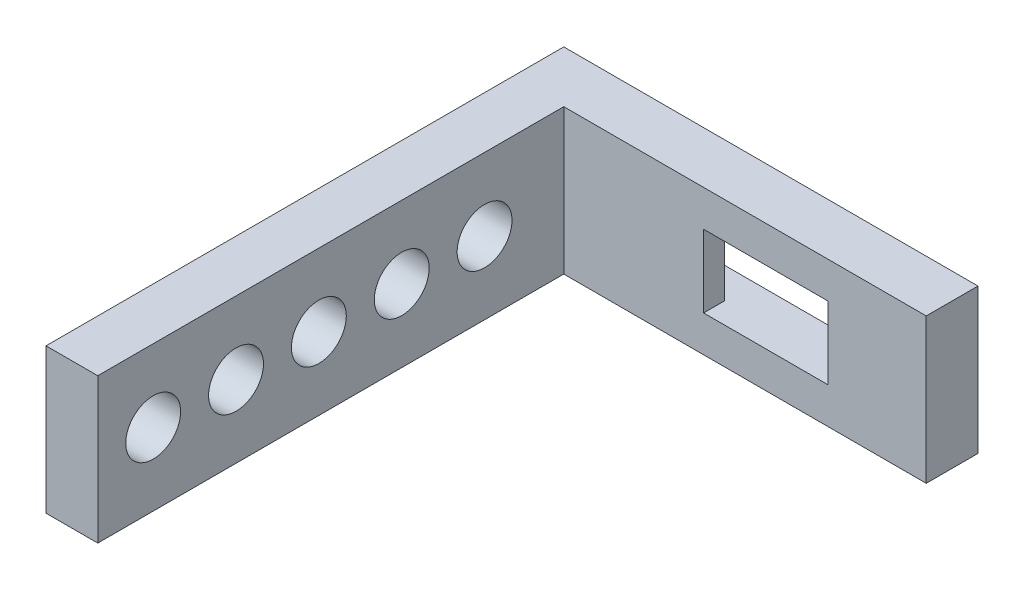
SolidWorks part; units mm, degrees
ref_plane "Front Plane" through (0, 0, 0) normal (0, 0, 1) x (1, 0, 0)
ref_plane "Top Plane" through (0, 0, 0) normal (0, 1, 0) x (1, 0, 0)
ref_plane "Right Plane" through (0, 0, 0) normal (1, 0, 0) x (0, 0, -1)
sketch "Sketch1" plane through (0, 0, 0) normal (0, 1, 0) x (1, 0, 0)
  line L2 (6.5891, 0) -> (10, 0)
  line L8 (0, 9) -> (11.5891, 9)
  line L10 (11.5891, 9) -> (40, 9)
  line L11 (40, 9) -> (40, 4)
  line L13 (6.5891, 0) -> (0, 0)
  line L15 (0, 0) -> (0, 9)
  line L17 (0, 0) -> (37.5449, 0) construction
  line L18 (10, 0) -> (10, 4)
  line L19 (10, 4) -> (40, 4)
  line L20 (25, 4) -> (25, 9) construction
  dimension "D2" = 25
  dimension "D4" = 30
  dimension "D9" = 5
  dimension "D10" = 4
extrude "Boss-Extrude1" add sketch "Sketch1" along normal blind 14
sketch "Sketch2" plane through (0, 0, -4) normal (0, 0, 1) x (1, 0, 0)
  line L0 (40, 7) -> (10, 7) construction
  line L1 (37.5, 3.5) -> (12.5, 3.5)
  line L2 (37.5, 3.5) -> (37.5, 10.5)
  line L3 (37.5, 10.5) -> (12.5, 10.5)
  line L4 (12.5, 3.5) -> (12.5, 10.5)
  line L6 (40, 14) -> (40, 0) construction
  line L7 (25, 3.5) -> (25, 10.5) construction
  line L8 (10, 14) -> (10, 0) construction
  line L11 (37.5, 7) -> (12.5, 7) construction
  line L14 (25, 14) -> (25, 0) construction
  line L15 (10, 14) -> (40, 14) construction
  line L16 (10, 0) -> (40, 0) construction
  dimension "D1" = 25
  dimension "D2" = 7
extrude "Cut-Extrude3" [suppressed] cut sketch "Sketch2" against normal blind 3
sketch "Sketch10" [suppressed] plane through (0, 0, -7) normal (0, 0, 1) x (1, 0, 0)
  line L0 (25, 10.5) -> (25, 3.5) construction
  line L1 (34, 9.5) -> (16, 9.5)
  line L2 (34, 9.5) -> (34, 4.5)
  line L3 (34, 4.5) -> (16, 4.5)
  line L4 (16, 9.5) -> (16, 4.5)
  line L5 (34, 9.5) -> (16, 4.5) construction
  line L6 (34, 4.5) -> (16, 9.5) construction
  line L7 (37.5, 10.5) -> (12.5, 10.5) construction
  line L8 (12.5, 3.5) -> (37.5, 3.5) construction
  line L9 (12.5, 7) -> (37.5, 7) construction
  line L10 (12.5, 10.5) -> (12.5, 3.5) construction
  line L11 (37.5, 3.5) -> (37.5, 10.5) construction
  point P0 (25, 7)
  point P11 (25, 9.5)
  point P18 (16, 7)
  dimension "D1" = 18
  dimension "D2" = 5
extrude "Cut-Extrude4" [suppressed] cut sketch "Sketch10" against normal through all
sketch "Sketch11" plane through (0, 0, 0) normal (-1, 0, 0) x (0, 0, 1)
  line L7 (-9, 14) -> (0, 14) construction
  line L12 (-5, 14) -> (-5, 24)
  line L18 (0, 14) -> (0, 15)
  line L20 (-5, 14) -> (0, 14)
  line L23 (-5, 24) -> (-2.8009, 24)
  line L24 (-2.8009, 24) -> (-2.8009, 15)
  line L25 (-2.8009, 15) -> (0, 15)
  dimension "D1" = 9
  dimension "D2" = 5
  dimension "D3" = 10
extrude "Boss-Extrude8" [suppressed] add sketch "Sketch11" against normal blind 3
sketch "Sketch12" [suppressed] plane through (3, 0, 0) normal (1, 0, 0) x (0, 0, -1)
  line L0 (2.8009, 15) -> (2.8009, 24) construction
  line L1 (8.4206, 15) -> (2.8009, 15) construction
  circle A0 centre (5.3009, 17.5) radius 2.5
  dimension "D1" = 5
extrude "Boss-Extrude9" [suppressed] add sketch "Sketch12" along normal blind 9
ref_plane "Plane1" through (10, 0, 0) normal (-1, 0, 0) x (0, 0, 1)
sketch "Sketch14" [suppressed] plane through (0, 0, -17.4206) normal (0, 0, -1) x (-1, 0, 0)
  line L0 (-59, 0) -> (0, 0) construction
  line L1 (-10, 0) -> (-3, 0)
  line L2 (-10, 0) -> (-10, 12)
  line L3 (-10, 12) -> (-3, 12)
  line L4 (-3, 0) -> (-3, 12)
  line L5 (-3, 24) -> (-3, 14) construction
  dimension "D1" = 12
  dimension "D2" = 7
sketch "Sketch15" [suppressed] plane through (0, 0, 0) normal (-1, 0, 0) x (0, 0, 1)
  line L1 (-8.1108, 24) -> (-8.1108, 15.2416) construction
  line L2 (-2.8009, 24) -> (-13.4206, 24) construction
  line L3 (-2.8009, 19.5) -> (-12.1862, 19.5) construction
  line L4 (-2.8009, 15) -> (-2.8009, 24) construction
  circle A0 centre (-8.1108, 19.5) radius 2.5
  dimension "D1" = 5
extrude "Cut-Extrude8" [suppressed] cut sketch "Sketch15" against normal through all
sketch "Sketch16" [suppressed] plane through (0, 0, -17.4206) normal (0, 0, -1) x (-1, 0, 0)
  line L0 (-59, 0) -> (0, 0) construction
  line L1 (-15, 11) -> (-3, 11)
  line L2 (-15, 11) -> (-15, 0)
  line L3 (-15, 0) -> (-3, 0)
  line L4 (-3, 11) -> (-3, 0)
  line L5 (-3, 24) -> (-3, 14) construction
  dimension "D1" = 12
  dimension "D2" = 11
extrude "Cut-Extrude9" [suppressed] cut sketch "Sketch16" against normal blind 9
sketch "Sketch19" [suppressed] plane through (0, 0, -17.4206) normal (0, 0, -1) x (-1, 0, 0)
  line L0 (-59, 0) -> (0, 0) construction
  line L1 (-13.7627, 0) -> (-3, 0)
  line L2 (-13.7627, 0) -> (-13.7627, 11.672)
  line L3 (-13.7627, 11.672) -> (-3, 11.672)
  line L4 (-3, 0) -> (-3, 11.672)
  line L5 (-3, 24) -> (-3, 14) construction
extrude "Cut-Extrude12" [suppressed] cut sketch "Sketch19" against normal blind 7
sketch "Sketch20" plane through (0, 0, 0) normal (-1, 0, 0) x (0, 0, 1)
  line L0 (-4, 14) -> (-4, 0) construction
  line L1 (0, 0) -> (41, 0)
  line L2 (0, 0) -> (0, 14)
  line L3 (0, 14) -> (41, 14)
  line L4 (41, 0) -> (41, 14)
  dimension "D1" = 45
extrude "Boss-Extrude10" add sketch "Sketch20" against normal blind 5
sketch "Sketch21" plane through (0, 0, 0) normal (-1, 0, 0) x (0, 0, 1)
  line L0 (-9, 14) -> (-9, 0) construction
  line L1 (-9, 7) -> (41, 7) construction
  line L2 (41, 0) -> (41, 14) construction
  circle A0 centre (-4.35, 7) radius 2.65
  circle A3 centre (3.65, 7) radius 2.65
  circle A4 centre (11.65, 7) radius 2.65
  circle A5 centre (19.65, 7) radius 2.65
  circle A6 centre (27.65, 7) radius 2.65
  circle A7 centre (35.65, 7) radius 2.65
  dimension "D1" = 5.3
  dimension "D2" = 4.65
  dimension "D3" = 4
  dimension "D4" = 3
extrude "Cut-Extrude13" cut sketch "Sketch21" against normal up to surface (5 mm away) contours A0 | A3 | A4 | A5 | A6 | A7 up to face at (5, 7, 20.5)
sketch "Sketch22" plane through (0, 14, 0) normal (0, 1, 0) x (1, 0, 0)
  line L0 (10, 4.95) -> (10, -4.95) construction
  line L1 (5, 0) -> (10, 0)
  line L2 (5, 0) -> (5, 4)
  line L3 (5, 4) -> (10, 4)
  line L4 (10, 0) -> (10, 4)
  line L5 (10, 4) -> (40, 4) construction
extrude "Cut-Extrude14" cut sketch "Sketch22" against normal through all
sketch "Sketch23" plane through (0, 0, 0) normal (-1, 0, 0) x (0, 0, 1)
  circle A0 centre (-4.35, 7) radius 2.65
extrude "Boss-Extrude11" add sketch "Sketch23" against normal up to surface (5 mm away) up to face at (5, 7, 1)
sketch "Sketch24" plane through (0, 0, -9) normal (0, 0, -1) x (-1, 0, 0)
  line L0 (0, 7) -> (-40, 7) construction
  line L1 (-12, 10.5) -> (-37, 10.5)
  line L2 (-12, 10.5) -> (-12, 3.5)
  line L3 (-12, 3.5) -> (-37, 3.5)
  line L4 (-37, 10.5) -> (-37, 3.5)
  line L5 (0, 14) -> (0, 0) construction
  line L6 (-40, 14) -> (-40, 0) construction
  point P10 (-12, 7)
  dimension "D1" = 25
  dimension "D2" = 7
  dimension "D3" = 3
extrude "Cut-Extrude15" cut sketch "Sketch24" against normal blind 3
sketch "Sketch25" plane through (0, 0, -6) normal (0, 0, -1) x (-1, 0, 0)
  line L0 (-24.5, 3.5) -> (-24.5, 10.5) construction
  line L1 (-18.5, 10.5) -> (-30.5, 10.5)
  line L2 (-18.5, 10.5) -> (-18.5, 3.5)
  line L3 (-18.5, 3.5) -> (-30.5, 3.5)
  line L4 (-30.5, 10.5) -> (-30.5, 3.5)
  line L5 (-18.5, 10.5) -> (-30.5, 3.5) construction
  line L6 (-18.5, 3.5) -> (-30.5, 10.5) construction
  line L7 (-37, 3.5) -> (-12, 3.5) construction
  line L8 (-12, 10.5) -> (-37, 10.5) construction
  line L9 (-37, 10.5) -> (-37, 3.5) construction
  point P0 (-24.5, 7)
  point P14 (-37, 7)
  point P15 (-30.5, 7)
  dimension "D1" = 12
  dimension "D2" = 7
extrude "Cut-Extrude16" cut sketch "Sketch25" against normal up to next
